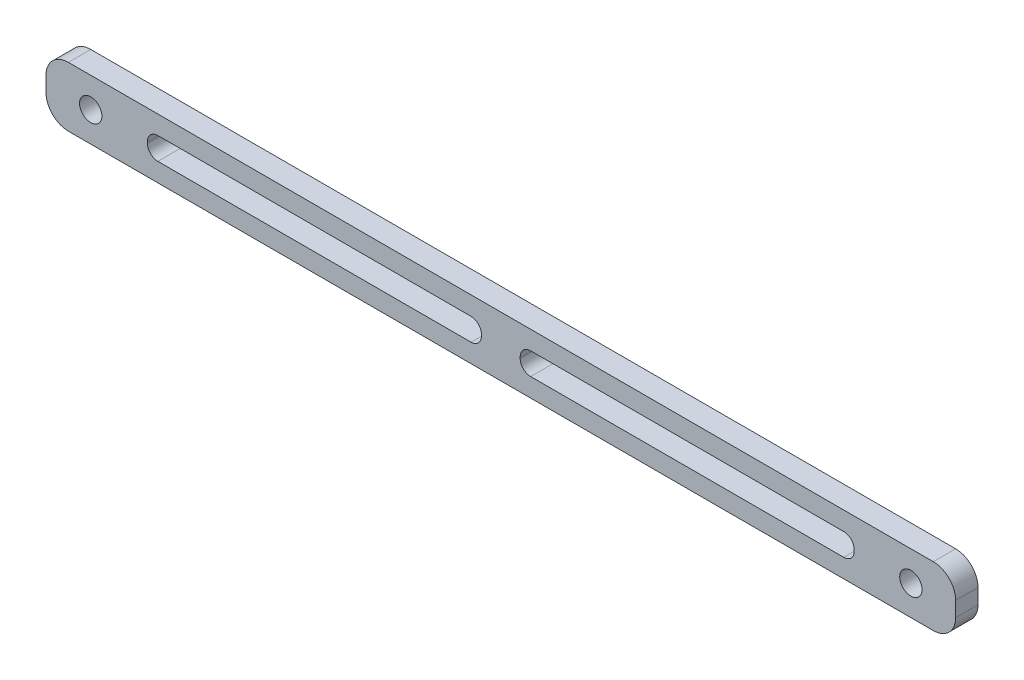
SolidWorks part; units mm, degrees
material "Maple"
ref_plane "Front Plane" through (0, 0, 0) normal (0, 0, 1) x (1, 0, 0)
ref_plane "Top Plane" through (0, 0, 0) normal (0, 1, 0) x (1, 0, 0)
ref_plane "Right Plane" through (0, 0, 0) normal (1, 0, 0) x (0, 0, -1)
sketch "Sketch1" plane through (0, 0, 0) normal (0, 0, 1) x (1, 0, 0)
  line L0 (0, 0) -> (-25, 0) construction
  line L1 (-58, 4) -> (58, 4)
  line L2 (-61, 1) -> (-61, -1)
  line L3 (-58, -4) -> (58, -4)
  line L4 (61, 1) -> (61, -1)
  line L5 (-61, 4) -> (61, -4) construction
  line L6 (-61, -4) -> (61, 4) construction
  line L7 (-46, 1.5) -> (-4, 1.5)
  line L8 (-47.4, 0.1) -> (-47.4, -0.1)
  line L9 (-46, -1.5) -> (-4, -1.5)
  line L10 (-2.6, 0.1) -> (-2.6, -0.1)
  line L11 (-47.4, 1.5) -> (-2.6, -1.5) construction
  line L12 (-47.6, -1.4933) -> (-2.6, 1.5) construction
  line L13 (4, 1.4943) -> (46, 1.4943)
  line L14 (2.6, 0.0943) -> (2.6, -0.0943)
  line L15 (4, -1.4943) -> (46, -1.4943)
  line L16 (47.4, 0.0943) -> (47.4, -0.0943)
  line L17 (2.6, 1.4943) -> (47.4, -1.4943) construction
  line L19 (0, 0) -> (25, 0) construction
  arc A0 (58, -4) -> (61, -1) centre (58, -1) ccw
  arc A1 (61, 1) -> (58, 4) centre (58, 1) ccw
  arc A2 (-58, -4) -> (-61, -1) centre (-58, -1) cw
  arc A3 (-58, 4) -> (-61, 1) centre (-58, 1) ccw
  circle A5 centre (-55, 0) radius 1.5
  circle A6 centre (55, 0) radius 1.5
  arc A7 (-2.6, -0.1) -> (-4, -1.5) centre (-4, -0.1) cw
  arc A8 (-2.6, 0.1) -> (-4, 1.5) centre (-4, 0.1) ccw
  arc A9 (-46, 1.5) -> (-47.4, 0.1) centre (-46, 0.1) ccw
  arc A10 (-46, -1.5) -> (-47.4, -0.1) centre (-46, -0.1) cw
  arc A11 (47.4, -0.0943) -> (46, -1.4943) centre (46, -0.0943) cw
  arc A12 (47.4, 0.0943) -> (46, 1.4943) centre (46, 0.0943) ccw
  arc A13 (4, 1.4943) -> (2.6, 0.0943) centre (4, 0.0943) ccw
  arc A14 (4, -1.4943) -> (2.6, -0.0943) centre (4, -0.0943) cw
  point P0 (0, 0)
  point P18 (0, 0)
  point P25 (0, 0)
  point P26 (-25, 0)
  point P45 (0, 0)
  point P46 (0, 0)
  point P47 (25, 0)
  point P60 (0, 0)
  dimension "D3" = 3
  dimension "D6" = 3
  dimension "D7" = 1.4
  dimension "D10" = 21
  dimension "D1" = 122
  dimension "D2" = 8
  dimension "D4" = 45
  dimension "D5" = 3
  dimension "D8" = 25
  dimension "D9" = 3
  dimension "D11" = 25
  dimension "D12" = 2.9887
  dimension "D13" = 110
  dimension "D14" = 55
extrude "Boss-Extrude1" add sketch "Sketch1" along normal blind 3
